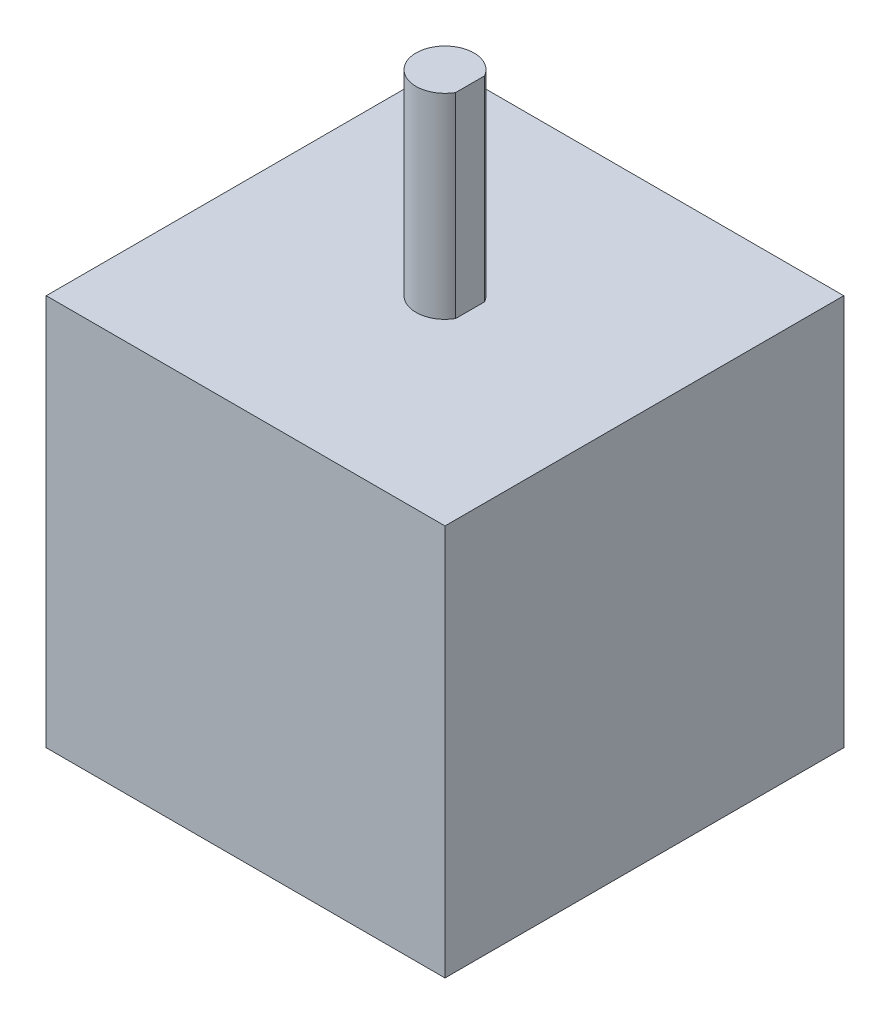
SolidWorks part; units mm, degrees
ref_plane "Front Plane" through (0, 0, 0) normal (0, 0, 1) x (1, 0, 0)
ref_plane "Top Plane" through (0, 0, 0) normal (0, 1, 0) x (1, 0, 0)
ref_plane "Right Plane" through (0, 0, 0) normal (1, 0, 0) x (0, 0, -1)
sketch "Sketch1" plane through (0, 0, 0) normal (0, 1, 0) x (1, 0, 0)
  line L1 (-27.5, -27.5) -> (27.5, -27.5)
  line L2 (-27.5, -27.5) -> (-27.5, 27.5)
  line L3 (-27.5, 27.5) -> (27.5, 27.5)
  line L4 (27.5, -27.5) -> (27.5, 27.5)
  line L5 (-27.5, -27.5) -> (27.5, 27.5) construction
  line L6 (-27.5, 27.5) -> (27.5, -27.5) construction
  point P0 (0, 0)
  dimension "D1" = 55
  dimension "D2" = 55
extrude "Boss-Extrude1" add sketch "Sketch1" along normal blind 54
sketch "Sketch2" plane through (0, 54, 0) normal (0, 1, 0) x (1, 0, 0)
  circle A0 centre (0, 0) radius 4
  dimension "D1" = 8
extrude "Boss-Extrude2" add sketch "Sketch2" along normal blind 27
sketch "Sketch3" plane through (0, 81, 0) normal (0, 1, 0) x (1, 0, 0)
  line L0 (3.4641, 2) -> (3.4641, -2)
  line L1 (3.4641, -2) -> (4.9249, -3.0674)
  line L2 (4.9249, -3.0674) -> (7.3808, 1.3902)
  line L3 (7.3808, 1.3902) -> (3.4641, 2)
  line L4 (-30.25, 0) -> (30.25, 0) construction
  circle A0 centre (0, 0) radius 4 construction
  dimension "D1" = 4
extrude "Cut-Extrude1" cut sketch "Sketch3" against normal blind 27
